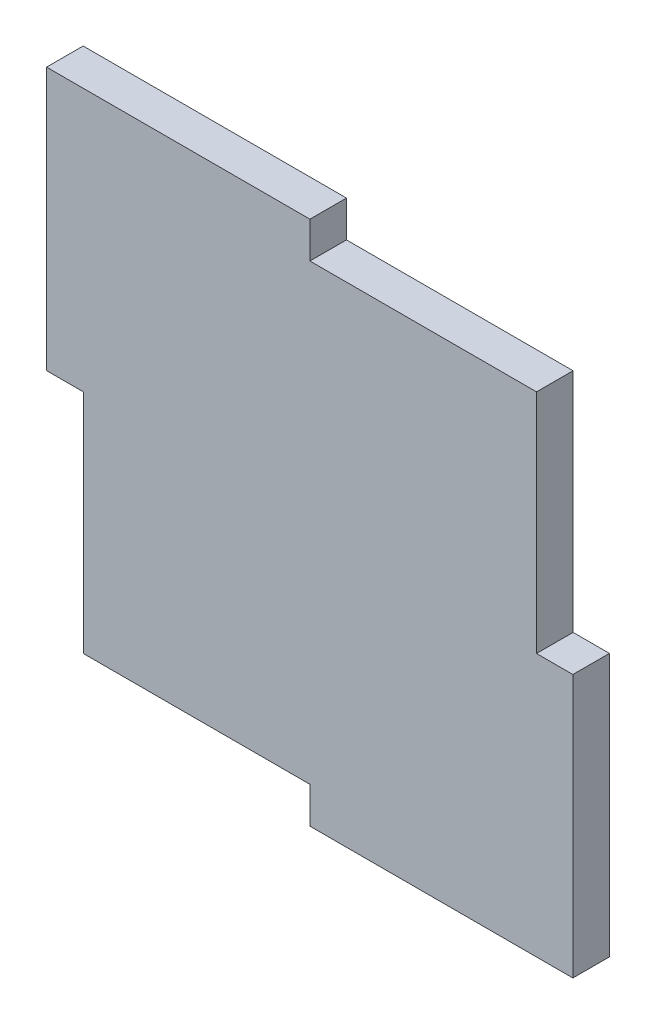
SolidWorks part; units mm, degrees
ref_plane "Front Plane" through (0, 0, 0) normal (0, 0, 1) x (1, 0, 0)
ref_plane "Top Plane" through (0, 0, 0) normal (0, 1, 0) x (1, 0, 0)
ref_plane "Right Plane" through (0, 0, 0) normal (1, 0, 0) x (0, 0, -1)
sketch "Sketch1" plane through (0, 0, 0) normal (0, 0, 1) x (1, 0, 0)
  line L0 (3.0896, 19.05) -> (3.0896, 0)
  line L1 (3.0896, 0) -> (22.1396, 0)
  line L2 (41.1896, 19.05) -> (41.1896, 38.1)
  line L3 (22.1396, 38.1) -> (41.1896, 38.1)
  line L4 (22.1396, 38.1) -> (22.1396, 41.148)
  line L5 (21.5713, 18.2733) -> (23.3574, 16.1539) construction
  line L6 (22.1396, 41.148) -> (0, 41.148)
  line L7 (0, 41.148) -> (0, 19.05)
  line L8 (0, 19.05) -> (3.0896, 19.05)
  line L9 (22.1396, 0) -> (22.1396, -3.048)
  line L10 (22.1396, -3.048) -> (44.2453, -3.048)
  line L11 (41.1896, 19.05) -> (44.2453, 19.05)
  line L12 (44.2453, 19.05) -> (44.2453, -3.048)
  dimension "D3" = 3.048
  dimension "D4" = 19.05
  dimension "D5" = 19.05
  dimension "D6" = 3.0557
  dimension "D10" = 22.098
  dimension "D9" = 22.098
  dimension "D1" = 22.1396
  dimension "D2" = 19.05
  dimension "D7" = 3.048
  dimension "D8" = 19.05
extrude "Boss-Extrude1" add sketch "Sketch1" along normal blind 3.0734
